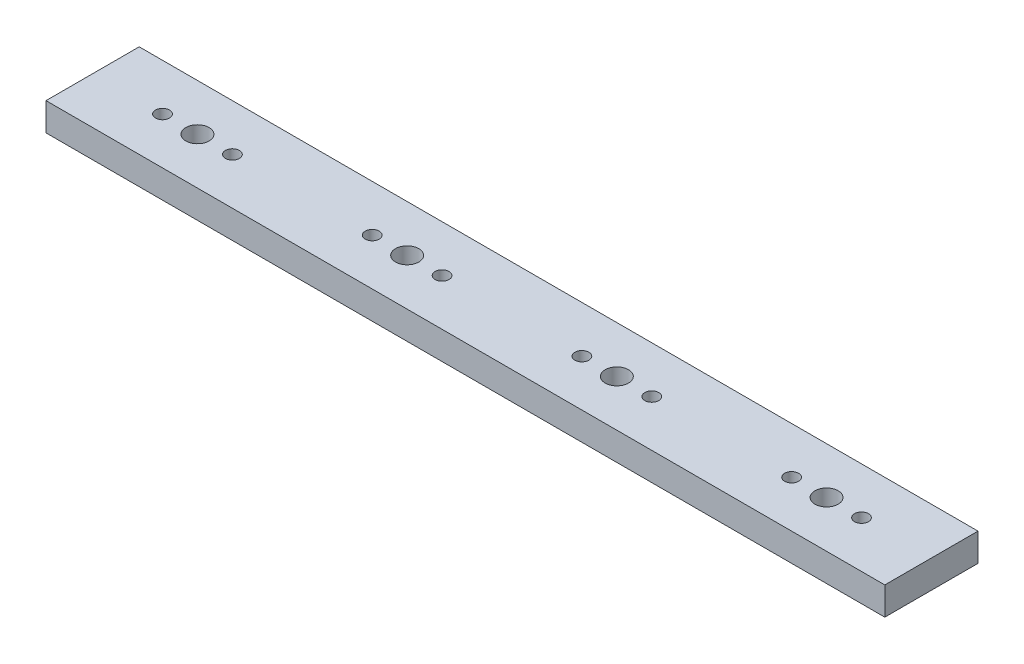
SolidWorks part; units mm, degrees
material "Beech"
ref_plane "Front Plane" through (0, 0, 0) normal (0, 0, 1) x (1, 0, 0)
ref_plane "Top Plane" through (0, 0, 0) normal (0, 1, 0) x (1, 0, 0)
ref_plane "Right Plane" through (0, 0, 0) normal (1, 0, 0) x (0, 0, -1)
sketch "Sketch1" plane through (0, 0, 0) normal (0, 1, 0) x (1, 0, 0)
  line L1 (-180, -20) -> (180, -20)
  line L2 (-180, -20) -> (-180, 20)
  line L3 (-180, 20) -> (180, 20)
  line L4 (180, -20) -> (180, 20)
  line L5 (-180, -20) -> (180, 20) construction
  line L6 (-180, 20) -> (180, -20) construction
  point P0 (0, 0)
  dimension "D1" = 40
  dimension "D2" = 360
extrude "Boss-Extrude1" add sketch "Sketch1" along normal blind 12
sketch "Sketch2" plane through (0, 12, 0) normal (0, 1, 0) x (1, 0, 0)
  line L0 (-180, 20) -> (-180, -20) construction
  circle A0 centre (-150, 0) radius 3
  circle A1 centre (-120, 0) radius 3
  circle A2 centre (-135, 0) radius 5
  dimension "D1" = 6
  dimension "D3" = 6
  dimension "D5" = 10
  dimension "D2" = 30
  dimension "D4" = 60
  dimension "D6" = 15
extrude "Cut-Extrude1" cut sketch "Sketch2" against normal up to next
pattern_linear "LPattern1" count 4 spacing 90 along (1, 0, 0) of "Cut-Extrude1"
